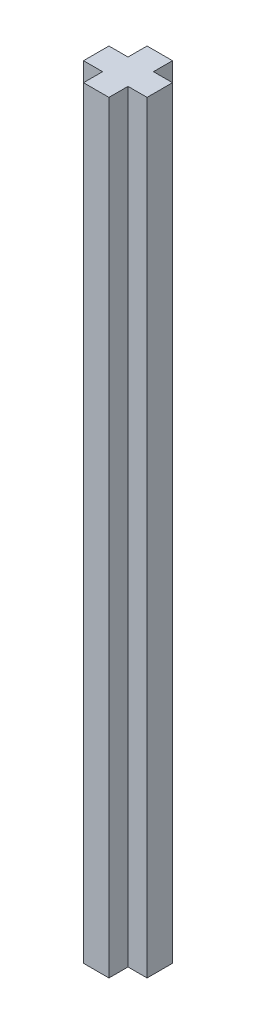
SolidWorks part; units mm, degrees
ref_plane "前视基准面" through (0, 0, 0) normal (0, 0, 1) x (1, 0, 0)
ref_plane "上视基准面" through (0, 0, 0) normal (0, 1, 0) x (1, 0, 0)
ref_plane "右视基准面" through (0, 0, 0) normal (1, 0, 0) x (0, 0, -1)
sketch "草图1" plane through (0, 0, 0) normal (0, 1, 0) x (1, 0, 0)
  line L0 (1, 1) -> (2.5, 1)
  line L1 (-1, 2.5) -> (1, 2.5)
  line L2 (-1, 2.5) -> (-1, 1)
  line L3 (-1, -2.5) -> (1, -2.5)
  line L4 (1, 2.5) -> (1, 1)
  line L7 (-2.5, 1) -> (-1, 1)
  line L8 (-2.5, 1) -> (-2.5, -1)
  line L9 (-2.5, -1) -> (-1, -1)
  line L10 (2.5, 1) -> (2.5, -1)
  line L15 (-1, -1) -> (-1, -2.5)
  line L17 (1, -1) -> (2.5, -1)
  line L19 (1, -1) -> (1, -2.5)
  point P0 (0, 0)
  point P6 (0, 0)
  dimension "D1" = 2
  dimension "D2" = 2
  dimension "D3" = 5
  dimension "D4" = 5
extrude "凸台-拉伸1" add sketch "草图1" along normal blind 60
